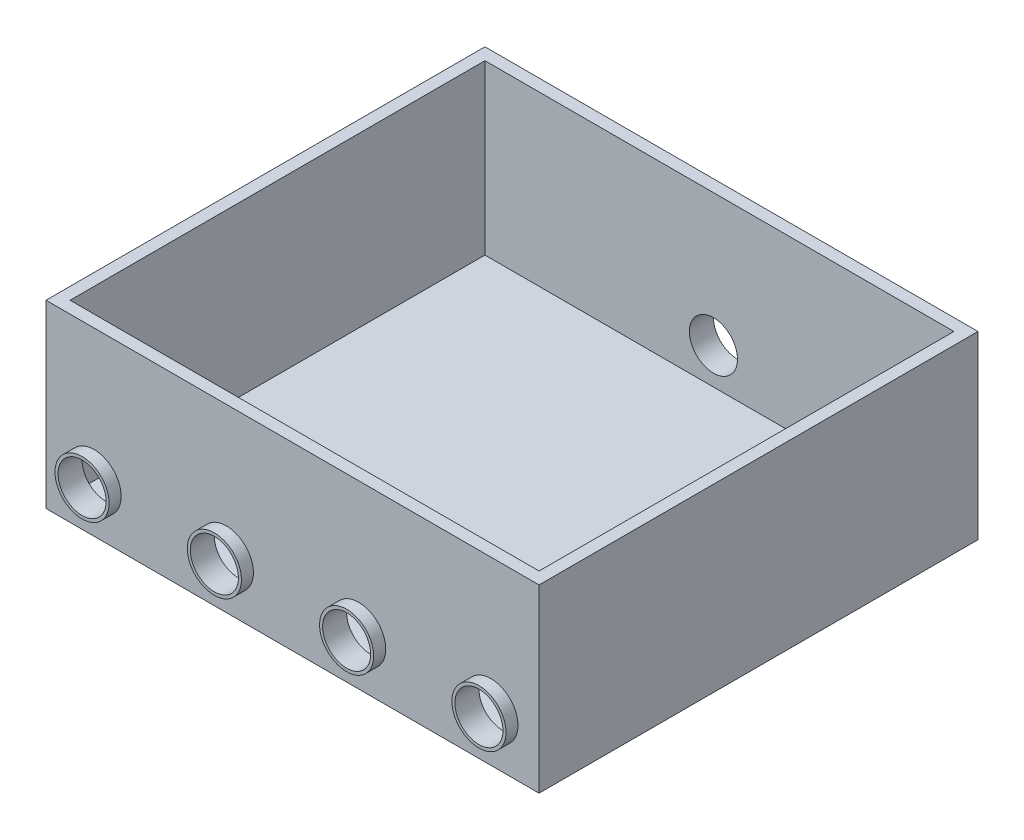
SolidWorks part; units mm, degrees
ref_plane "Front Plane" through (0, 0, 0) normal (0, 0, 1) x (1, 0, 0)
ref_plane "Top Plane" through (0, 0, 0) normal (0, 1, 0) x (1, 0, 0)
ref_plane "Right Plane" through (0, 0, 0) normal (1, 0, 0) x (0, 0, -1)
sketch "Sketch1" plane through (0, 0, 0) normal (0, 1, 0) x (1, 0, 0)
  line L1 (0, 0) -> (1041.4, 0)
  line L2 (0, 0) -> (0, 927.1)
  line L3 (0, 927.1) -> (1041.4, 927.1)
  line L4 (1041.4, 0) -> (1041.4, 927.1)
  dimension "D1" = 1041.4
  dimension "D2" = 927.1
extrude "Boss-Extrude1" add sketch "Sketch1" along normal blind 508
sketch "Sketch3" plane through (0, 0, 0) normal (0, 0, 1) x (1, 0, 0)
  line L1 (0, 508) -> (0, 0) construction
  line L2 (0, 0) -> (1041.4, 0) construction
  line L4 (0, 508) -> (1041.4, 508) construction
  circle A0 centre (101.6, 101.6) radius 57.15
  circle A1 centre (381, 101.6) radius 57.15
  circle A2 centre (660.4, 101.6) radius 57.15
  circle A3 centre (939.8, 101.6) radius 57.15
  dimension "D2" = 114.3
  dimension "D4" = 114.3
  dimension "D6" = 114.3
  dimension "D8" = 114.3
  dimension "D1" = 101.6
  dimension "D3" = 101.6
  dimension "D5" = 279.4
  dimension "D7" = 279.4
  dimension "D9" = 279.4
  dimension "D10" = 406.4
  dimension "D11" = 406.4
  dimension "D12" = 406.4
extrude "Boss-Extrude2" add sketch "Sketch3" along normal blind 25.4
sketch "Sketch4" plane through (0, 0, -927.1) normal (0, 0, -1) x (-1, 0, 0)
  line L0 (-1041.4, 508) -> (-1041.4, 0) construction
  line L1 (-1041.4, 508) -> (0, 508) construction
  circle A0 centre (-508, 101.6) radius 57.15
  dimension "D1" = 114.3
  dimension "D2" = 533.4
  dimension "D3" = 406.4
extrude "Boss-Extrude3" add sketch "Sketch4" along normal blind 25.4
sketch "Sketch5" plane through (0, 508, 0) normal (0, 1, 0) x (1, 0, 0)
  line L0 (0, 0) -> (1041.4, 0) construction
  line L1 (1016, 901.7) -> (25.4, 901.7)
  line L2 (1016, 901.7) -> (1016, 25.4)
  line L3 (1016, 25.4) -> (25.4, 25.4)
  line L4 (25.4, 901.7) -> (25.4, 25.4)
  line L5 (1041.4, 0) -> (1041.4, 927.1) construction
  line L6 (1041.4, 927.1) -> (0, 927.1) construction
  line L7 (0, 927.1) -> (0, 0) construction
  dimension "D1" = 25.4
  dimension "D2" = 25.4
  dimension "D3" = 25.4
  dimension "D4" = 25.4
extrude "Cut-Extrude1" cut sketch "Sketch5" against normal blind 482.6
sketch "Sketch6" plane through (0, 0, 25.4) normal (0, 0, 1) x (1, 0, 0)
  circle A0 centre (101.6, 101.6) radius 50.8
  circle A1 centre (381, 101.6) radius 50.8
  circle A2 centre (660.4, 101.6) radius 50.8
  circle A3 centre (939.8, 101.6) radius 50.8
  dimension "D1" = 101.6
  dimension "D2" = 101.6
  dimension "D3" = 101.6
  dimension "D4" = 101.6
extrude "Cut-Extrude2" cut sketch "Sketch6" against normal blind 127
sketch "Sketch7" plane through (0, 0, -952.5) normal (0, 0, -1) x (-1, 0, 0)
  circle A0 centre (-508, 101.6) radius 50.8
  dimension "D1" = 101.6
extrude "Cut-Extrude3" cut sketch "Sketch7" against normal blind 127
sketch "Sketch8" plane through (0, 0, 0) normal (-1, 0, 0) x (0, 0, 1)
  line L0 (0, 508) -> (0, 0) construction
  line L1 (-927.1, 508) -> (0, 508)
  line L2 (-927.1, 508) -> (-927.1, 381)
  line L3 (-927.1, 381) -> (0, 381)
  line L4 (0, 508) -> (0, 381)
  dimension "D1" = 127
extrude "Cut-Extrude4" cut sketch "Sketch8" against normal blind 1041.4
